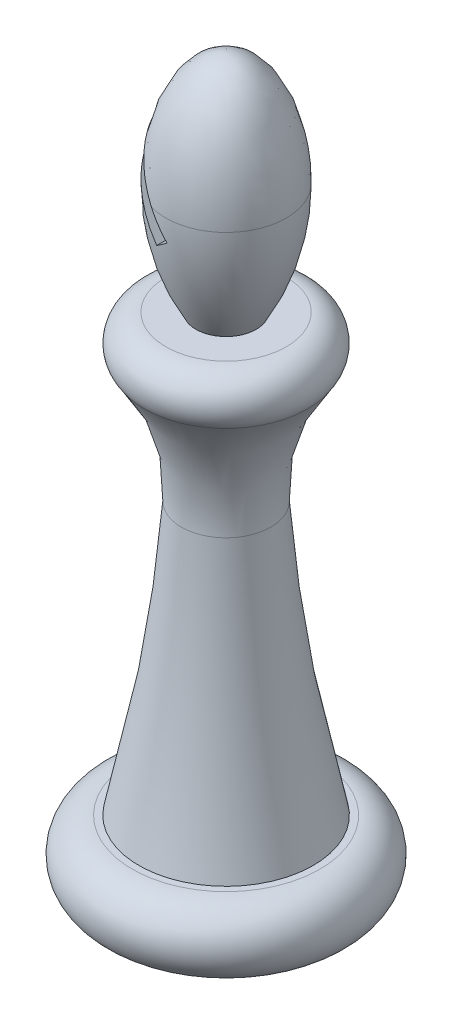
SolidWorks part; units mm, degrees
ref_plane "Front Plane" through (0, 0, 0) normal (0, 0, 1) x (1, 0, 0)
ref_plane "Top Plane" through (0, 0, 0) normal (0, 1, 0) x (1, 0, 0)
ref_plane "Right Plane" through (0, 0, 0) normal (1, 0, 0) x (0, 0, -1)
sketch "Sketch1" plane through (0, 0, 0) normal (0, 0, 1) x (1, 0, 0)
  line L0 (0, -0.5697) -> (0, 40.4585) construction
  line L1 (0, 27.8579) -> (3.4052, 27.8579)
  line L2 (3.4052, 24.8258) -> (2.3107, 24.8258)
  line L3 (0, 3.2295) -> (5.2988, 3.2295)
  line L4 (5.2988, -0.5697) -> (0, -0.5697)
  line L5 (0, 40.4585) -> (0, -0.5697)
  arc A1 (3.4052, 27.8579) -> (3.4052, 24.8258) centre (3.4052, 26.3418) cw
  arc A2 (5.2988, 3.2295) -> (5.2988, -0.5697) centre (5.2988, 1.3299) cw
  arc A3 (3.4052, 34.1582) -> (1.7026, 27.8579) centre (-9.103, 34.1582) cw
  arc A4 (2.3107, 24.8258) -> (4.93, 3.2295) centre (92.65, 24.8258) ccw
  ellipse E0 centre (0, 34.1582) end of major axis (0, 27.8579) minor radius 3.4052 (3.4052, 34.1582) -> (0, 40.4585) ccw
  point P16 (2.3107, 24.8258)
revolve "Revolve1" add sketch "Sketch1" angle 360 about L0
sketch "Sketch2" plane through (0, 0, 0) normal (0, 0, 1) x (1, 0, 0)
  line L4 (-3.0632, 36.9101) -> (0, 32.9038)
  line L5 (0, 32.9038) -> (-0.7336, 32.3429)
  line L6 (-0.7336, 32.3429) -> (-3.3015, 35.7015)
  line L8 (-3.0632, 36.9101) -> (-4.0403, 37.8873)
  line L9 (-4.0403, 37.8873) -> (-4.9651, 35.9854)
  line L10 (-4.9651, 35.9854) -> (-3.3015, 35.7015)
  ellipse E0 centre (0, 34.1582) end of major axis (0, 40.4585) minor radius 3.4052 (0, 40.4585) -> (-3.4052, 34.1582) ccw construction
extrude "Cut-Extrude1" cut sketch "Sketch2" against normal mid plane 10
fillet "Fillet1" radius 10 1 edges at (0, 24.8258, -2.3107)
